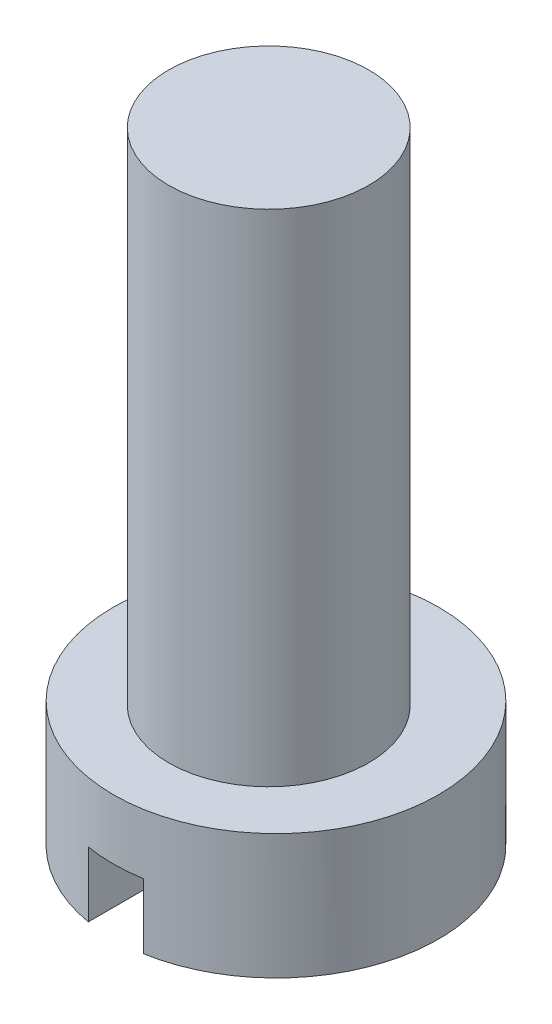
SolidWorks part; units mm, degrees
material "AISI 1020"
ref_plane "Спереди" through (0, 0, 0) normal (0, 0, 1) x (1, 0, 0)
ref_plane "Сверху" through (0, 0, 0) normal (0, 1, 0) x (1, 0, 0)
ref_plane "Справа" through (0, 0, 0) normal (1, 0, 0) x (0, 0, -1)
sketch "Эскиз1" plane through (0, 0, 0) normal (0, 1, 0) x (1, 0, 0)
  circle A0 centre (0, 0) radius 6.5
  dimension "D1" = 13
extrude "Бобышка-Вытянуть1" add sketch "Эскиз1" along normal blind 5
sketch "Эскиз2" plane through (0, 0, 0) normal (0, 0, 1) x (1, 0, 0)
  line L0 (-6.5, 0) -> (6.5, 0) construction
  line L1 (-1.1, 2.6) -> (1.1, 2.6)
  line L2 (-1.1, 2.6) -> (-1.1, 0)
  line L3 (-1.1, 0) -> (1.1, 0)
  line L4 (1.1, 2.6) -> (1.1, 0)
  dimension "D1" = 2.2
  dimension "D2" = 2.6
extrude "Вырез-Вытянуть1" cut sketch "Эскиз2" against normal mid plane 13.9
sketch "Эскиз3" plane through (0, 5, 0) normal (0, 1, 0) x (1, 0, 0)
  circle A0 centre (0, -0.2911) radius 4
  dimension "D1" = 8
extrude "Бобышка-Вытянуть2" add sketch "Эскиз3" along normal blind 20
cosmetic thread "Условное изображение резьбы1" parameters "D2"=6.891
